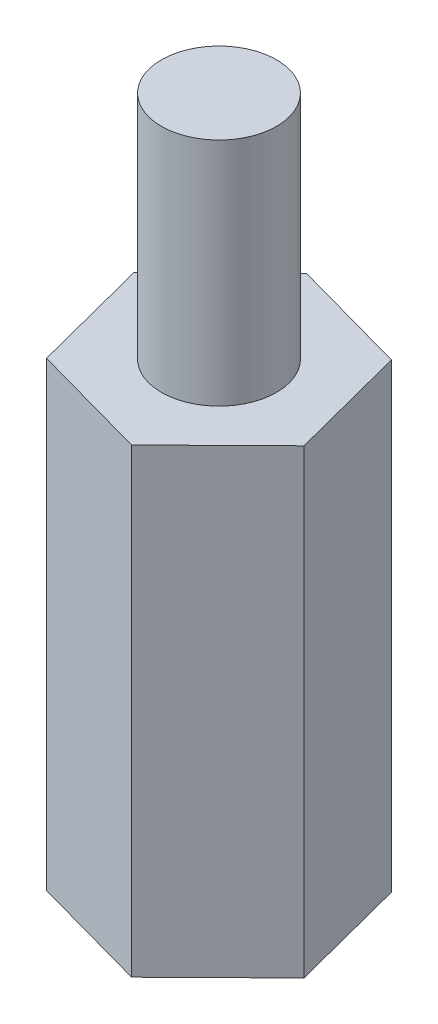
SolidWorks part; units mm, degrees
material "Brass"
ref_plane "Front Plane" through (0, 0, 0) normal (0, 0, 1) x (1, 0, 0)
ref_plane "Top Plane" through (0, 0, 0) normal (0, 1, 0) x (1, 0, 0)
ref_plane "Right Plane" through (0, 0, 0) normal (1, 0, 0) x (0, 0, -1)
sketch "Sketch1" plane through (0, 0, 0) normal (0, 1, 0) x (1, 0, 0)
  line L1 (0.7972, -3.0737) -> (3.0605, -0.8464)
  line L2 (3.0605, -0.8464) -> (2.2633, 2.2273)
  line L3 (2.2633, 2.2273) -> (-0.7972, 3.0737)
  line L4 (-0.7972, 3.0737) -> (-3.0605, 0.8464)
  line L5 (-3.0605, 0.8464) -> (-2.2633, -2.2273)
  line L6 (-2.2633, -2.2273) -> (0.7972, -3.0737)
  circle A0 centre (0, 0) radius 2.75 construction
  dimension "D1" = 5.5
extrude "Boss-Extrude1" add sketch "Sketch1" along normal blind 12
sketch "Sketch2" plane through (0, 12, 0) normal (0, 1, 0) x (1, 0, 0)
  circle A0 centre (0, 0) radius 1.5
  dimension "D1" = 3
extrude "Boss-Extrude2" add sketch "Sketch2" along normal blind 6
sketch "Sketch3" plane through (0, 0, 0) normal (0, -1, 0) x (1, 0, 0)
  circle A0 centre (0, 0) radius 1.5
  dimension "D1" = 3
extrude "Cut-Extrude2" cut sketch "Sketch3" against normal blind 6
